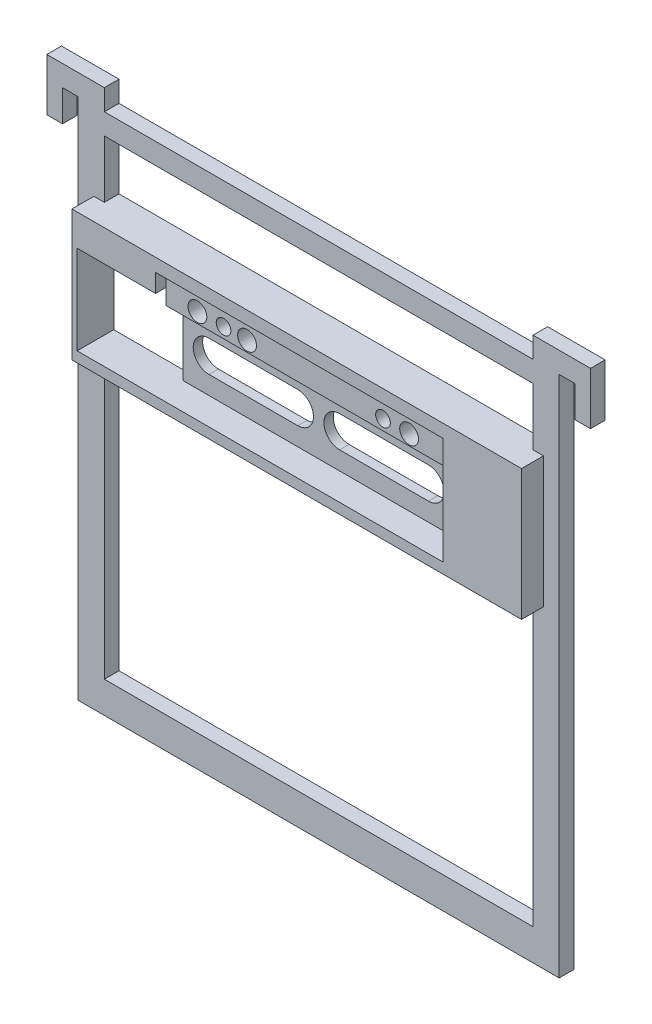
SolidWorks part; units mm, degrees
ref_plane "前视基准面" through (0, 0, 0) normal (0, 0, 1) x (1, 0, 0)
ref_plane "上视基准面" through (0, 0, 0) normal (0, 1, 0) x (1, 0, 0)
ref_plane "右视基准面" through (0, 0, 0) normal (1, 0, 0) x (0, 0, -1)
other "Configuration Table"
sketch "草图1" plane through (0, 0, 0) normal (0, 0, 1) x (1, 0, 0)
  line L1 (0, 0) -> (86, 0)
  line L2 (0, 0) -> (0, 25)
  line L3 (0, 25) -> (86, 25)
  line L4 (86, 0) -> (86, 25)
  dimension "D1" = 86
  dimension "D2" = 25
extrude "凸台-拉伸1" add sketch "草图1" along normal blind 7
sketch "草图2" plane through (0, 0, 7) normal (0, 0, 1) x (1, 0, 0)
  line L0 (0, 25) -> (0, 0) construction
  line L1 (1, 19) -> (16, 19)
  line L2 (1, 19) -> (1, 2)
  line L3 (1, 2) -> (16, 2)
  line L4 (16, 19) -> (16, 2)
  line L5 (86, 25) -> (0, 25) construction
  dimension "D1" = 15
  dimension "D2" = 17
  dimension "D3" = 1
  dimension "D4" = 6
extrude "切除-拉伸1" cut sketch "草图2" against normal through all
sketch "草图3" plane through (0, 0, 7) normal (0, 0, 1) x (1, 0, 0)
  line L1 (16, 2) -> (71, 2)
  line L2 (16, 2) -> (16, 15)
  line L3 (16, 15) -> (71, 15)
  line L4 (71, 2) -> (71, 15)
  dimension "D1" = 55
  dimension "D2" = 13
extrude "切除-拉伸2" cut sketch "草图3" against normal blind 5.2
sketch "草图4" plane through (0, 0, 7) normal (0, 0, 1) x (1, 0, 0)
  line L0 (71, 2) -> (71, 15) construction
  line L1 (16, 15) -> (71, 15)
  line L2 (16, 15) -> (16, 22.5)
  line L3 (16, 22.5) -> (71, 22.5)
  line L4 (71, 15) -> (71, 22.5)
  dimension "D1" = 7.5
extrude "切除-拉伸3" cut sketch "草图4" against normal blind 2
sketch "草图5" plane through (0, 0, 5) normal (0, 0, 1) x (1, 0, 0)
  line L0 (71, 22.5) -> (16, 22.5) construction
  line L1 (16, 22.5) -> (16, 19) construction
  circle A0 centre (22, 18) radius 1.8
  circle A1 centre (31.5, 18) radius 1.8
  circle A2 centre (62.5, 18) radius 1.8
  dimension "D1" = 3.6
  dimension "D2" = 4.5
  dimension "D3" = 9.5
  dimension "D4" = 31
  dimension "D5" = 6
extrude "切除-拉伸4" cut sketch "草图5" against normal through all
sketch "草图6" plane through (0, 0, 5) normal (0, 0, 1) x (1, 0, 0)
  line L0 (16, 19) -> (16, 15) construction
  line L1 (71, 22.5) -> (16, 22.5) construction
  circle A0 centre (27, 18) radius 1.4
  circle A1 centre (57.5, 18) radius 1.4
  dimension "D1" = 2.8
  dimension "D2" = 11
  dimension "D3" = 4.5
  dimension "D4" = 41.5
extrude "切除-拉伸5" cut sketch "草图6" against normal through all
sketch "草图7" plane through (0, 0, 1.8) normal (0, 0, 1) x (1, 0, 0)
  line L0 (21, 8.5) -> (38, 8.5) construction
  line L1 (21, 11.5) -> (38, 11.5)
  line L2 (21, 5.5) -> (38, 5.5)
  line L3 (46, 8.5) -> (63, 8.5) construction
  line L4 (46, 11.5) -> (63, 11.5)
  line L5 (46, 5.5) -> (63, 5.5)
  line L6 (16, 15) -> (16, 2) construction
  arc A0 (21, 11.5) -> (21, 5.5) centre (21, 8.5) ccw
  arc A1 (38, 5.5) -> (38, 11.5) centre (38, 8.5) ccw
  arc A2 (46, 11.5) -> (46, 5.5) centre (46, 8.5) ccw
  arc A3 (63, 5.5) -> (63, 11.5) centre (63, 8.5) ccw
  point P2 (29.5, 8.5)
  point P9 (54.5, 8.5)
  point P16 (16, 8.5)
  dimension "D2" = 3
  dimension "D6" = 3
  dimension "D1" = 5
  dimension "D3" = 17
  dimension "D4" = 8
  dimension "D5" = 17
extrude "切除-拉伸6" cut sketch "草图7" against normal through all
chamfer "倒角1" distance 1 angle 45 1 edges at (43.5, 15, 5)
sketch "草图9" plane through (0, 0, 0) normal (0, 0, -1) x (-1, 0, 0)
  line L0 (0, 25) -> (0, 0) construction
  line L15 (0, 0) -> (-86, 0) construction
  line L34 (-86, 25) -> (0, 25) construction
  line L35 (-86, 0) -> (0, 0)
  line L36 (-95, 34) -> (-92, 34)
  line L37 (-92, 34) -> (-92, 40)
  line L38 (-92, 40) -> (-89, 40)
  line L39 (-89, 40) -> (-89, -60)
  line L40 (-89, -60) -> (3, -60)
  line L41 (3, -60) -> (3, 40)
  line L42 (3, 40) -> (6, 40)
  line L43 (6, 40) -> (6, 34)
  line L44 (6, 34) -> (9, 34)
  line L45 (9, 34) -> (9, 44)
  line L46 (9, 44) -> (-2, 44)
  line L47 (-2, 44) -> (-2, 40)
  line L48 (-2, 40) -> (-84, 40)
  line L49 (-84, 40) -> (-84, 44)
  line L50 (-84, 44) -> (-95, 44)
  line L51 (-95, 44) -> (-95, 34)
  line L52 (-86, 0) -> (-86, 25) construction
  line L53 (-84, 25) -> (-86, 25)
  line L54 (0, 0) -> (0, 25)
  line L55 (0, 25) -> (-2, 25)
  line L56 (-86, 25) -> (-86, 0)
  line L58 (-84, -2) -> (-2, -2)
  line L59 (-84, -2) -> (-84, -54)
  line L60 (-84, -54) -> (-2, -54)
  line L61 (-2, -2) -> (-2, -54)
  line L62 (-84, 36) -> (-2, 36)
  line L63 (-84, 36) -> (-84, 25)
  line L65 (-2, 36) -> (-2, 25)
  point P24 (-92, 37)
  dimension "D1" = 3
  dimension "D2" = 3
  dimension "D3" = 60
  dimension "D4" = 15
  dimension "D5" = 3
  dimension "D6" = 3
  dimension "D7" = 4
  dimension "D8" = 10
  dimension "D9" = 5
  dimension "D10" = 5
  dimension "D11" = 3
  dimension "D12" = 3
  dimension "D13" = 2
  dimension "D14" = 6
  dimension "D15" = 4
extrude "凸台-拉伸2" add sketch "草图9" against normal blind 2.8
